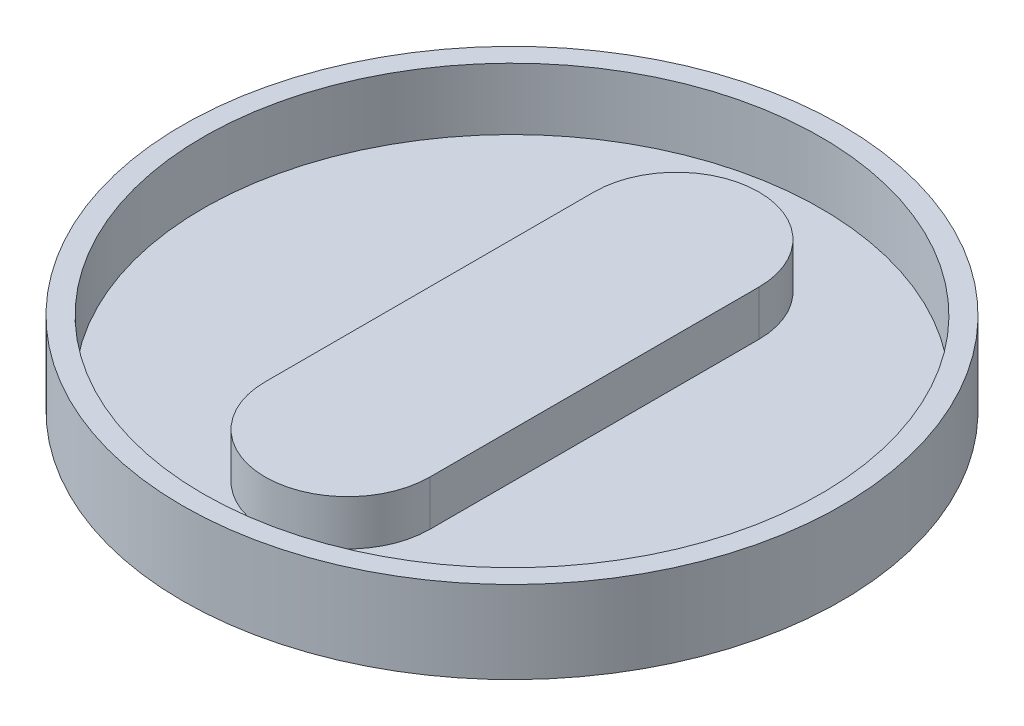
SolidWorks part; units mm, degrees
ref_plane "Front Plane" through (0, 0, 0) normal (0, 0, 1) x (1, 0, 0)
ref_plane "Top Plane" through (0, 0, 0) normal (0, 1, 0) x (1, 0, 0)
ref_plane "Right Plane" through (0, 0, 0) normal (1, 0, 0) x (0, 0, -1)
sketch "Sketch1" plane through (0, 0, 0) normal (0, 1, 0) x (1, 0, 0)
  circle A0 centre (0, 0) radius 101.6
  dimension "D1" = 203.2
extrude "Boss-Extrude1" add sketch "Sketch1" along normal blind 25.4
sketch "Sketch3" plane through (0, 25.4, 0) normal (0, 1, 0) x (1, 0, 0)
  circle A0 centre (0, 0) radius 95.25
extrude "Cut-Extrude1" cut sketch "Sketch3" against normal blind 19.05
sketch "Sketch5" plane through (0, 6.35, 0) normal (0, 1, 0) x (1, 0, 0)
  line L0 (0, -50.7079) -> (0, 50.7079) construction
  line L1 (-25.4, -50.7079) -> (-25.4, 50.7079)
  line L2 (25.4, -50.7079) -> (25.4, 50.7079)
  arc A0 (-25.4, -50.7079) -> (25.4, -50.7079) centre (0, -50.7079) ccw
  arc A1 (25.4, 50.7079) -> (-25.4, 50.7079) centre (0, 50.7079) ccw
  point P2 (0, 0)
  dimension "D1" = 101.4159
  dimension "D2" = 25.4
extrude "Boss-Extrude2" add sketch "Sketch5" along normal blind 13.97
